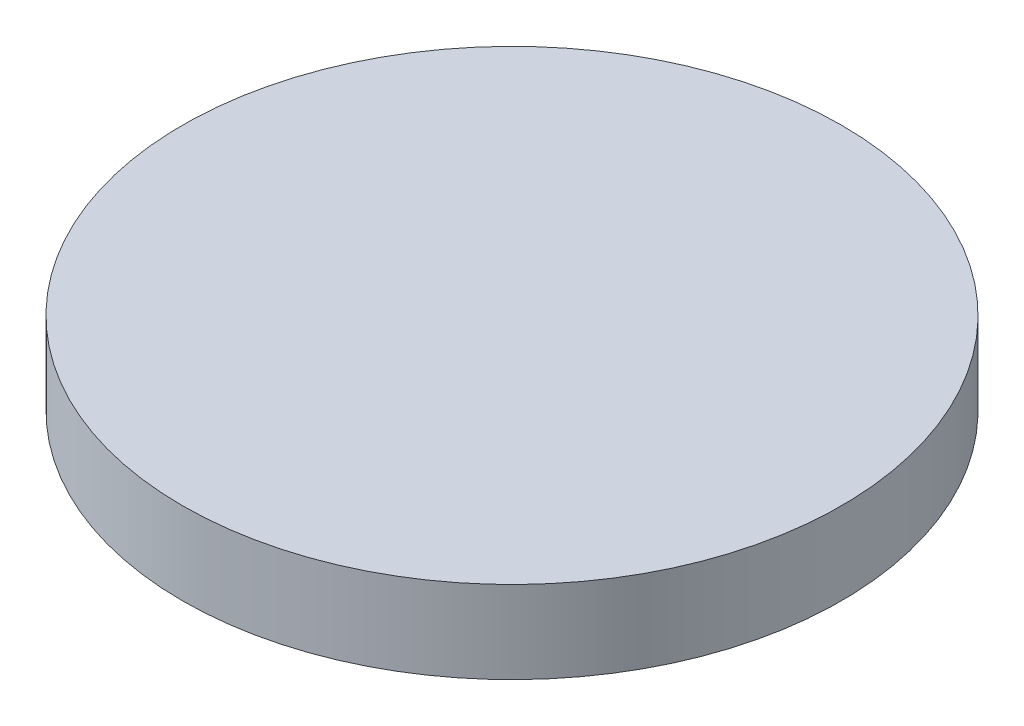
SolidWorks part; units mm, degrees
ref_plane "Front Plane" through (0, 0, 0) normal (0, 0, 1) x (1, 0, 0)
ref_plane "Top Plane" through (0, 0, 0) normal (0, 1, 0) x (1, 0, 0)
ref_plane "Right Plane" through (0, 0, 0) normal (1, 0, 0) x (0, 0, -1)
sketch "Sketch1" plane through (0, 0, 0) normal (0, 1, 0) x (1, 0, 0)
  circle A0 centre (0, 0) radius 76.2
  dimension "D1" = 152.4
extrude "Boss-Extrude1" add sketch "Sketch1" along normal blind 19.05
